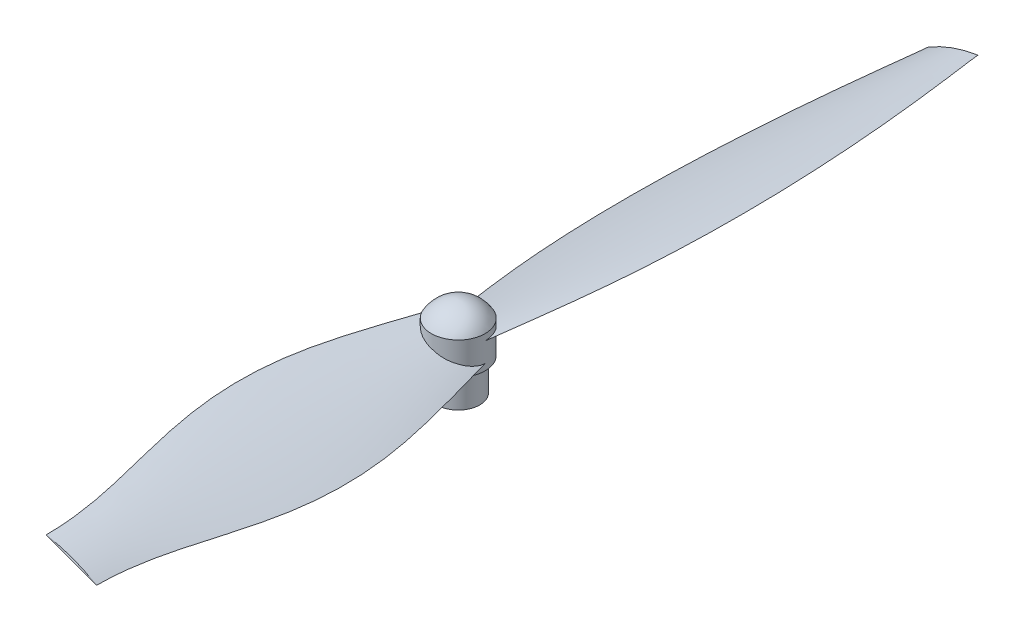
SolidWorks part; units mm, degrees
material "ABS"
ref_plane "正面" through (0, 0, 0) normal (0, 0, 1) x (1, 0, 0)
ref_plane "平面" through (0, 0, 0) normal (0, 1, 0) x (1, 0, 0)
ref_plane "右側面" through (0, 0, 0) normal (1, 0, 0) x (0, 0, -1)
sketch "ｽｹｯﾁ1" plane through (0, 0, 0) normal (0, 0, 1) x (1, 0, 0)
  line L0 (0, 0) -> (20.811, 0) construction
  line L1 (0, 0) -> (0, 12.9538) construction
  line L2 (0, 0) -> (0, 15)
  line L3 (0, 0) -> (4, 0)
  line L4 (4, 0) -> (4, 6)
  line L5 (4, 6) -> (5, 6)
  line L6 (5, 6) -> (5, 12)
  arc A0 (0, 15) -> (5, 12) centre (-0.198, 9.0033) cw
  dimension "D6" = 6
  dimension "D1" = 15
  dimension "D2" = 4
  dimension "D3" = 6
  dimension "D4" = 1
  dimension "D5" = 6
revolve "回転1" add sketch "ｽｹｯﾁ1" angle 360 about L2
sketch "ｽｹｯﾁ2" plane through (0, 0, 0) normal (0, -1, 0) x (1, 0, 0)
  line L1 (1.5282, -2.4491) -> (2.8851, 0.0989)
  line L2 (2.8851, 0.0989) -> (1.3568, 2.548)
  line L3 (1.3568, 2.548) -> (-1.5282, 2.4491)
  line L4 (-1.5282, 2.4491) -> (-2.8851, -0.0989)
  line L5 (-2.8851, -0.0989) -> (-1.3568, -2.548)
  line L6 (-1.3568, -2.548) -> (1.5282, -2.4491)
  circle A0 centre (0, 0) radius 2.5 construction
  dimension "D1" = 5
extrude "ｶｯﾄ - 押し出し1" cut sketch "ｽｹｯﾁ2" against normal blind 7
ref_plane "平面1" through (0, 0, 20) normal (0, 0, 1) x (1, 0, 0)
ref_plane "平面2" through (0, 0, 72) normal (0, 0, 1) x (1, 0, 0)
sketch "ｽｹｯﾁ3" plane through (0, 0, 0) normal (0, 0, 1) x (1, 0, 0)
  line L0 (0, 15) -> (0, 0) construction
  line L1 (-5, 10.8199) -> (5, 7.1801)
  arc A0 (-5, 10.8199) -> (5, 7.1801) centre (-8.3546, -13.9541) cw
  point P7 (0, 9)
  dimension "D4" = 25
  dimension "D1" = 10
  dimension "D2" = 70
  dimension "D3" = 9
sketch "ｽｹｯﾁ4" plane through (0, 0, 20) normal (0, 0, 1) x (1, 0, 0)
  line L0 (0, 15) -> (0, 0) construction
  line L1 (-4, 0) -> (4, 0) construction
  line L2 (-9, 12.2757) -> (9, 5.7243)
  arc A0 (-9, 12.2757) -> (9, 5.7243) centre (-27.1648, -65.6347) cw
  point P8 (0, 9)
  dimension "D4" = 80
  dimension "D1" = 18
  dimension "D2" = 70
  dimension "D3" = 9
sketch "ｽｹｯﾁ5" plane through (0, 0, 72) normal (0, 0, 1) x (1, 0, 0)
  line L0 (0, 15) -> (0, 0) construction
  line L1 (-4.6985, 10.7101) -> (4.6985, 7.2899)
  arc A0 (-4.6985, 10.7101) -> (4.6985, 7.2899) centre (-8.3777, -14.0177) cw
  point P7 (0, 9)
  dimension "D4" = 25
  dimension "D1" = 10
  dimension "D2" = 70
  dimension "D3" = 9
surface "ｻｰﾌｪｽ-ﾛﾌﾄ1"
ref_plane "平面3" through (0, 0, -20) normal (0, 0, 1) x (1, 0, 0)
ref_plane "平面4" through (0, 0, -92) normal (0, 0, 1) x (1, 0, 0)
sketch "ｽｹｯﾁ6" plane through (0, 0, 0) normal (0, 0, 1) x (1, 0, 0)
  line L0 (0, 15) -> (0, 0) construction
  line L1 (5, 10.8199) -> (-5, 7.1801)
  line L2 (-4, 0) -> (4, 0) construction
  arc A0 (5, 10.8199) -> (-5, 7.1801) centre (8.3546, -13.9541) ccw
  point P7 (0, 9)
  dimension "D4" = 25
  dimension "D1" = 10
  dimension "D2" = 70
  dimension "D3" = 9
sketch "ｽｹｯﾁ7" plane through (0, 0, -20) normal (0, 0, 1) x (1, 0, 0)
  line L0 (0, 15) -> (0, 0) construction
  line L1 (9, 12.2757) -> (-9, 5.7243)
  arc A0 (9, 12.2757) -> (-9, 5.7243) centre (27.1648, -65.6347) ccw
  point P7 (0, 9)
  dimension "D4" = 80
  dimension "D1" = 18
  dimension "D2" = 70
  dimension "D3" = 9
sketch "ｽｹｯﾁ8" plane through (0, 0, -92) normal (0, 0, 1) x (1, 0, 0)
  line L0 (0, 15) -> (0, 0) construction
  line L1 (4.6985, 10.7101) -> (-4.6985, 7.2899)
  arc A0 (4.6985, 10.7101) -> (-4.6985, 7.2899) centre (8.3777, -14.0177) ccw
  point P7 (0, 9)
  dimension "D4" = 25
  dimension "D1" = 10
  dimension "D2" = 70
  dimension "D3" = 9
surface "ｻｰﾌｪｽ-ﾛﾌﾄ2"
